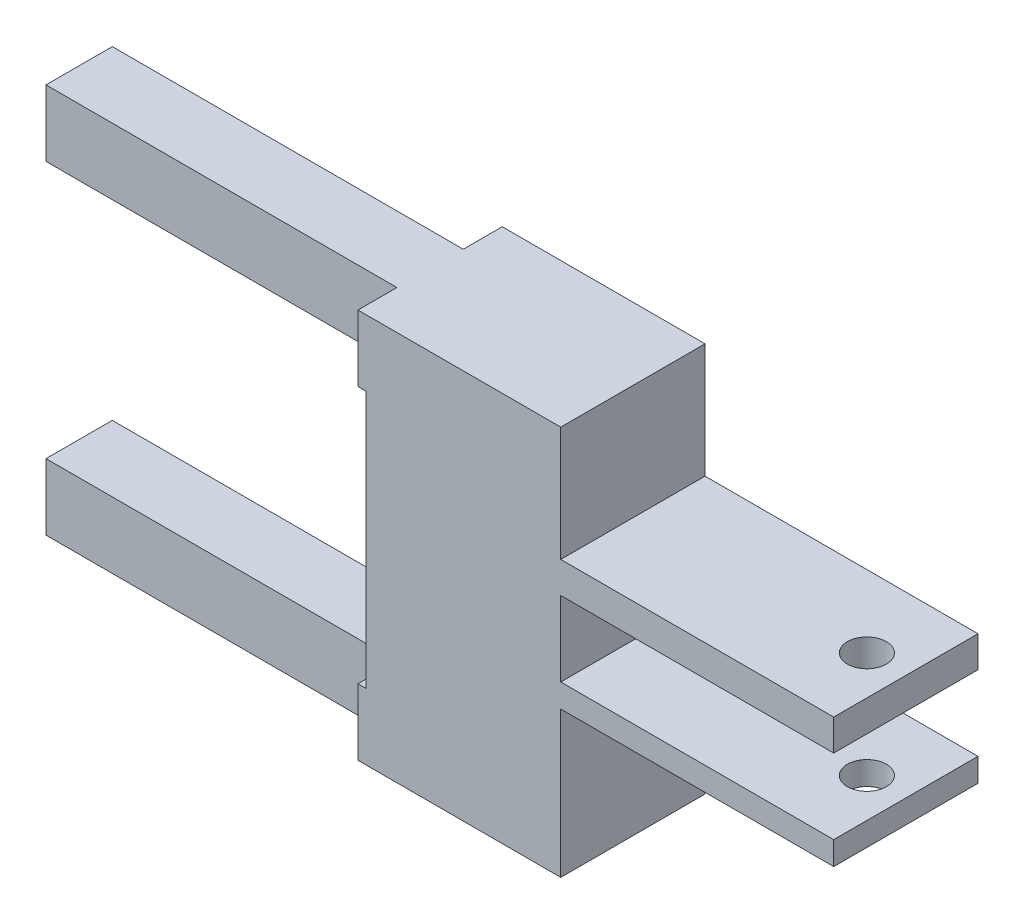
SolidWorks part; units mm, degrees
ref_plane "前视基准面" through (0, 0, 0) normal (0, 0, 1) x (1, 0, 0)
ref_plane "上视基准面" through (0, 0, 0) normal (0, 1, 0) x (1, 0, 0)
ref_plane "右视基准面" through (0, 0, 0) normal (1, 0, 0) x (0, 0, -1)
other "Configuration Table"
sketch "草图1" plane through (0, 0, 0) normal (0, 0, 1) x (1, 0, 0)
  line L0 (25, 12.61) -> (25, -12.61) construction
  line L1 (-25, 50) -> (25, 50)
  line L2 (-25, 50) -> (-25, -50)
  line L3 (-25, -50) -> (25, -50)
  line L4 (25, 50) -> (25, -50)
  line L5 (-25, 50) -> (25, -50) construction
  line L6 (-25, -50) -> (25, 50) construction
  line L7 (-25, 50) -> (-117, 50)
  line L8 (-25, 50) -> (-25, 33)
  line L9 (-25, 33) -> (-117, 33)
  line L10 (-117, 50) -> (-117, 33)
  line L11 (-25, -50) -> (-117, -50)
  line L12 (-25, -50) -> (-25, -33)
  line L13 (-25, -33) -> (-117, -33)
  line L14 (-117, -50) -> (-117, -33)
  line L16 (25, 12.61) -> (95, 12.61)
  line L17 (25, 12.61) -> (25, 20.61)
  line L18 (25, 20.61) -> (95, 20.61)
  line L19 (95, 12.61) -> (95, 20.61)
  line L20 (25, -12.61) -> (95, -12.61)
  line L21 (25, -12.61) -> (25, -6.61)
  line L22 (25, -6.61) -> (95, -6.61)
  line L23 (95, -12.61) -> (95, -6.61)
  point P0 (0, 0)
  point P15 (25, 0)
extrude "凸台-拉伸1" add sketch "草图1" along normal blind 37 contours L7 L10 L9 L2 | L14 L11 L2 L13 | L19 L16 L4 L18 | L20 L23 L22 L4 | L4 L1 L2 L3 L21
sketch "草图2" plane through (0, 20.61, 0) normal (0, 1, 0) x (1, 0, 0)
  line L0 (95, -18.5) -> (85, -18.5) construction
  line L1 (95, -37) -> (95, 0) construction
  circle A0 centre (85, -18.5) radius 5
extrude "切除-拉伸1" cut sketch "草图2" against normal through all
sketch "草图3" plane through (-117, 0, 0) normal (-1, 0, 0) x (0, 0, 1)
  line L0 (18.5, 50) -> (18.5, 33) construction
  line L1 (37, 50) -> (0, 50) construction
  line L2 (37, 33) -> (0, 33) construction
  line L3 (18.5, -33) -> (18.5, -50) construction
  line L4 (37, -33) -> (0, -33) construction
  line L5 (37, -50) -> (0, -50) construction
  line L6 (27, 33) -> (37, 33)
  line L8 (10, 50) -> (10, 33)
  line L10 (27, 50) -> (27, 33)
  line L11 (10, 50) -> (27, 33) construction
  line L12 (10, 33) -> (27, 50) construction
  line L13 (10, -33) -> (27, -33)
  line L14 (10, -33) -> (10, -50)
  line L16 (27, -33) -> (27, -50)
  line L17 (10, -33) -> (27, -50) construction
  line L18 (10, -50) -> (27, -33) construction
  line L19 (0, 50) -> (10, 50)
  line L20 (0, 50) -> (0, 33)
  line L21 (0, 33) -> (10, 33)
  line L22 (37, 50) -> (37, 33)
  line L23 (0, 50) -> (37, 33) construction
  line L24 (0, 33) -> (37, 50) construction
  line L25 (0, -33) -> (37, -33)
  line L26 (0, -33) -> (0, -50)
  line L27 (0, -50) -> (10, -50)
  line L28 (37, -33) -> (37, -50)
  line L29 (0, -33) -> (37, -50) construction
  line L30 (0, -50) -> (37, -33) construction
  line L31 (27, 50) -> (37, 50)
  line L32 (27, -50) -> (37, -50)
  point P12 (18.5, 41.5)
  point P17 (18.5, -41.5)
  point P22 (18.5, 41.5)
  point P28 (18.5, -41.5)
  line M14 (0, 33) -> (37, 33)
  line M15 (37, 33) -> (37, 50)
  line M16 (37, 50) -> (0, 50)
extrude "切除-拉伸2" cut sketch "草图3" against normal blind 90 contours L26 L27 L14 L25 | L16 L32 L28 L25 | L10 M16 M14 M15 | L20 L21 L8 L19
